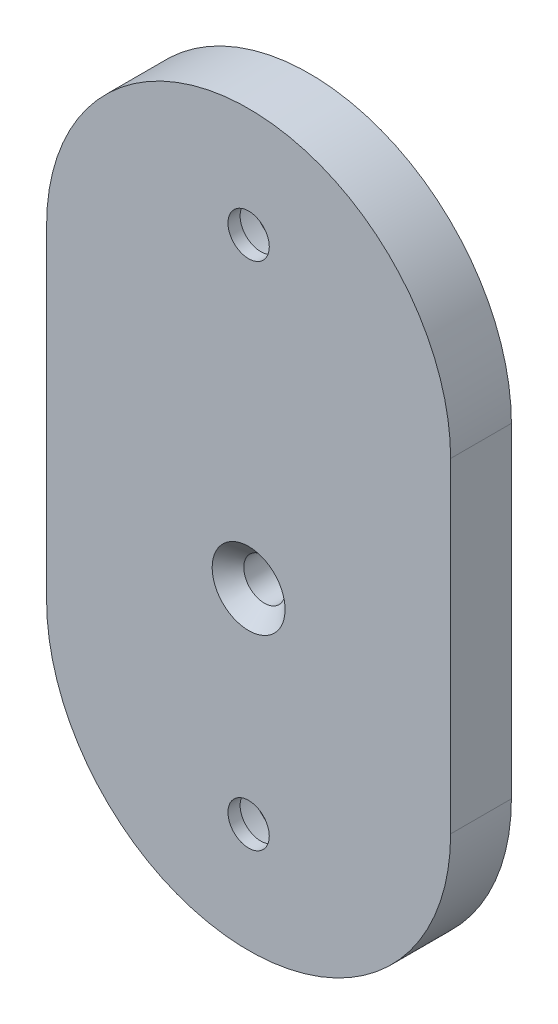
SolidWorks part; units mm, degrees
material "1060 Alloy"
ref_plane "Front Plane" through (0, 0, 0) normal (0, 0, 1) x (1, 0, 0)
ref_plane "Top Plane" through (0, 0, 0) normal (0, 1, 0) x (1, 0, 0)
ref_plane "Right Plane" through (0, 0, 0) normal (1, 0, 0) x (0, 0, -1)
sketch "Sketch1" plane through (0, 0, 0) normal (0, 0, 1) x (1, 0, 0)
  line L0 (-16.6225, -13.377) -> (-16.6225, 13.377)
  line L1 (-16.6225, 13.377) -> (16.6225, 13.377) construction
  line L2 (16.6225, 13.377) -> (16.6225, -13.377)
  line L3 (-16.6225, -13.377) -> (16.6225, -13.377) construction
  line L4 (0, 29.9995) -> (0, -29.9995) construction
  line L5 (0, 21) -> (0, -21) construction
  arc A0 (-16.6225, 13.377) -> (16.6225, 13.377) centre (0, 13.377) cw
  arc A1 (16.6225, -13.377) -> (-16.6225, -13.377) centre (0, -13.377) cw
  circle A2 centre (0, -21) radius 1.7
  circle A3 centre (0, 21) radius 1.7
  point P6 (0, 0)
  point P14 (0, 0)
  dimension "D3" = 3.4
  dimension "D1" = 33.245
  dimension "D2" = 59.999
  dimension "D4" = 42
extrude "Boss-Extrude1" add sketch "Sketch1" along normal blind 5
ref_point "Point1"
ref_point "Point2"
ref_plane "Plane1" through (0, 0, 0) normal (1, 0, 0) x (0, 0, -1)
sketch "Sketch2" plane through (0, 0, 0) normal (1, 0, 0) x (0, 0, -1)
  line L0 (-5, -21) -> (0, -21) construction
  line L2 (0, -22.7) -> (0, -19.3) construction
  line L3 (-2.5, -4.2) -> (-11.1293, -4.2) construction
  line L4 (0, -4.2) -> (-5, -4.2)
  line L5 (0, 13.377) -> (0, -13.377) construction
  line L6 (-5, -4.2) -> (-5, -7.2)
  line L7 (-5, 13.377) -> (-5, -13.377) construction
  line L8 (-5, -7.2) -> (-3.7, -5.9)
  line L9 (-3.7, -5.9) -> (0, -5.9)
  line L10 (0, -5.9) -> (0, -4.2)
  line L11 (-2.5, -21) -> (-2.5, -4.2) construction
  dimension "D3" = 3.4
  dimension "D1" = 16.8
  dimension "D4" = 45
revolve "Cut-Revolve1" cut sketch "Sketch2" angle 360 about L3
sketch "Sketch3" plane through (0, 0, 0) normal (0, 0, -1) x (-1, 0, 0)
  circle A0 centre (0, 21) radius 5
  circle A1 centre (0, -21) radius 5
  dimension "D1" = 10
extrude "Cut-Extrude1" cut sketch "Sketch3" against normal blind 4
chamfer "Chamfer1" distance 0.3 angle 45 2 edges at (-5, -21, 0) (-5, 21, 0)
equation "\"L\"=0.042000"
equation "\"H\"=0.059999"
equation "\"B\"=0.033245"
equation "\"T\"=0.005000"
equation "\"D1@Sketch1\"=\"B\"*1000"
equation "\"D2@Sketch1\"=\"H\"*1000"
equation "\"D3@Sketch1\"=\"bolt_hole_diameter\"*1000"
equation "\"D4@Sketch1\"=\"L\"*1000"
equation "\"D1@Boss-Extrude1\"=\"T\"*1000"
equation "\"bearing_hole_diameter\"=0.010000"
equation "\"spring_arm_hole_pos\"=0.016800"
equation "\"spring_arm_hole_max_diam\"=0.006000"
equation "\"spring_arm_hole_min_diam\"=0.003400"
equation "\"arm_hole_head_height\"=0.001650"
equation "\"D2@Sketch2\"=\"spring_arm_hole_max_diam\"*1000"
equation "\"D3@Sketch2\"=\"spring_arm_hole_min_diam\"*1000"
equation "\"D1@Sketch2\"=\"spring_arm_hole_pos\"*1000"
equation "\"bolt_hole_diameter\"=0.003400"
equation "\"bearing_depth\"=0.004000"
equation "\"D1@Sketch3\"=\"bearing_hole_diameter\"*1000"
equation "\"D1@Cut-Extrude1\"=\"bearing_depth\"*1000"
